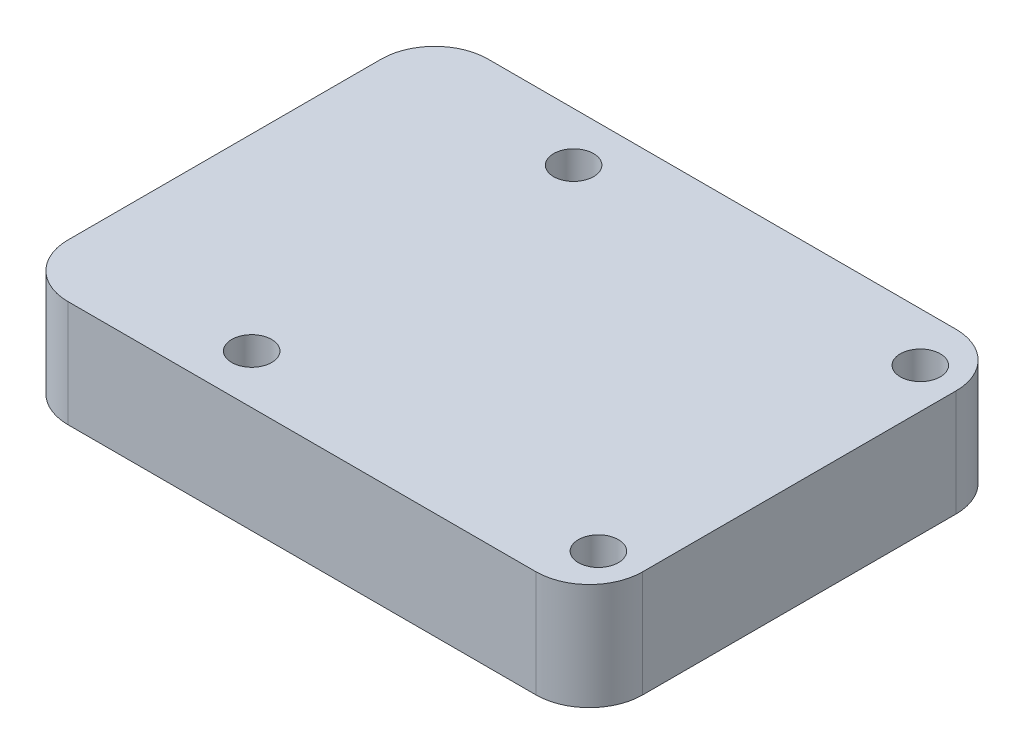
SolidWorks part; units mm, degrees
ref_plane "前视基准面" through (0, 0, 0) normal (0, 0, 1) x (1, 0, 0)
ref_plane "上视基准面" through (0, 0, 0) normal (0, 1, 0) x (1, 0, 0)
ref_plane "右视基准面" through (0, 0, 0) normal (1, 0, 0) x (0, 0, -1)
other "Configuration Table"
sketch "草图1" plane through (0, 0, 0) normal (0, 1, 0) x (1, 0, 0)
  line L0 (-13, 0) -> (13, 0) construction
  line L1 (-13, 12.07) -> (13, 12.07) construction
  line L2 (-13, 12.07) -> (-13, -12.07) construction
  line L3 (-13, -12.07) -> (13, -12.07) construction
  line L4 (13, 12.07) -> (13, -12.07) construction
  line L5 (-13, 12.07) -> (13, -12.07) construction
  line L6 (-13, -12.07) -> (13, 12.07) construction
  line L7 (-27.1, 15.75) -> (16, 15.75)
  line L8 (-27.1, 15.75) -> (-27.1, -15.75)
  line L9 (-27.1, -15.75) -> (16, -15.75)
  line L10 (16, 15.75) -> (16, -15.75)
  circle A0 centre (-13, 12.07) radius 1.5
  circle A1 centre (13, 12.07) radius 1.5
  circle A2 centre (13, -12.07) radius 1.5
  circle A3 centre (-13, -12.07) radius 1.5
  point P0 (0, 0)
  dimension "D3" = 3
  dimension "D1" = 26
  dimension "D2" = 24.14
  dimension "D4" = 3
  dimension "D5" = 43.1
  dimension "D6" = 31.5
extrude "凸台-拉伸1" add sketch "草图1" along normal blind 8
fillet "圆角1" radius 4 4 edges at (16, 4, -15.75) (16, 4, 15.75) (-27.1, 4, -15.75) (-27.1, 4, 15.75)
